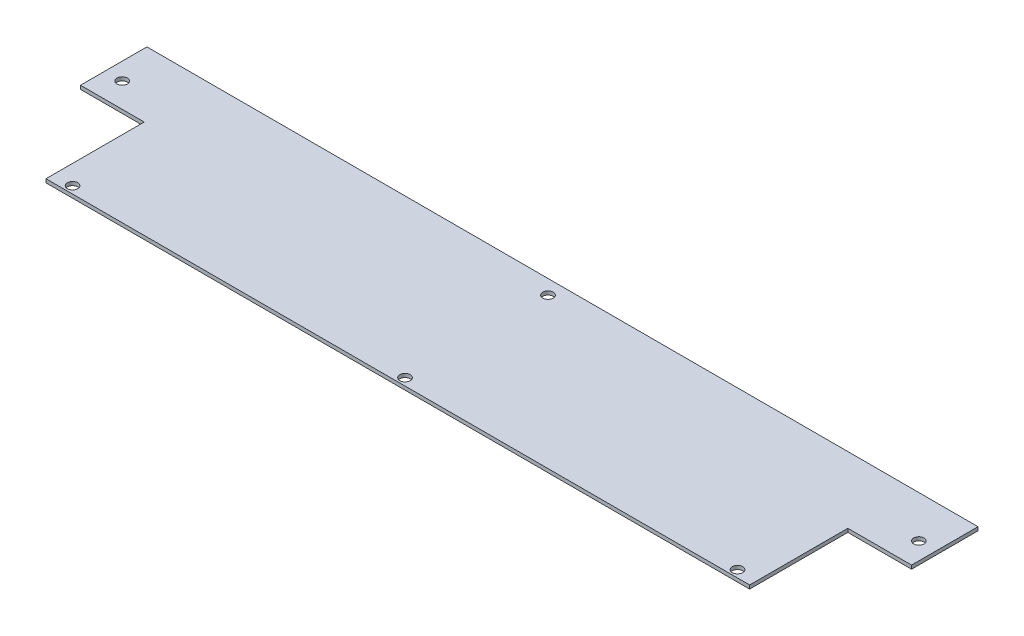
SolidWorks part; units mm, degrees
ref_plane "Front Plane" through (0, 0, 0) normal (0, 0, 1) x (1, 0, 0)
ref_plane "Top Plane" through (0, 0, 0) normal (0, 1, 0) x (1, 0, 0)
ref_plane "Right Plane" through (0, 0, 0) normal (1, 0, 0) x (0, 0, -1)
sketch "Sketch1" plane through (0, 0, 0) normal (0, 1, 0) x (1, 0, 0)
  line L0 (0, 0) -> (0, -33.02) construction
  line L1 (190.5, -36.195) -> (-190.5, -36.195) construction
  line L2 (190.5, -36.195) -> (190.5, 36.195) construction
  line L3 (190.5, 36.195) -> (-190.5, 36.195) construction
  line L4 (-190.5, -36.195) -> (-190.5, 36.195) construction
  line L5 (190.5, -36.195) -> (-190.5, 36.195) construction
  line L6 (190.5, 36.195) -> (-190.5, -36.195) construction
  line L7 (-146.177, -33.02) -> (146.177, -33.02) construction
  line L8 (0, 0) -> (0, 29.845) construction
  line L27 (0, 0) -> (0, 17.78) construction
  line L34 (-175.1457, 17.78) -> (175.1457, 17.78) construction
  line L35 (-154.686, -36.195) -> (-154.686, 6.985)
  line L48 (154.686, -36.195) -> (154.686, 6.985)
  line L49 (154.686, -36.195) -> (-154.686, -36.195)
  line L50 (-154.686, 6.985) -> (-182.7083, 6.985)
  line L52 (-182.7083, 36.195) -> (-182.7083, 6.985)
  line L53 (-182.7083, 36.195) -> (182.7083, 36.195)
  line L54 (182.7083, 36.195) -> (182.7083, 6.985)
  line L55 (182.7083, 6.985) -> (154.686, 6.985)
  circle A0 centre (175.1457, 17.78) radius 2.286
  circle A1 centre (0, 29.845) radius 2.286
  circle A2 centre (146.177, -33.02) radius 2.286
  circle A3 centre (-175.1457, 17.78) radius 2.286
  circle A4 centre (0, -33.02) radius 2.286
  circle A5 centre (-146.177, -33.02) radius 2.286
  point P0 (0, 0)
  point P10 (0, -33.02)
  point P17 (-184.4888, 3.81)
  point P18 (-240.3437, -33.02)
  point P20 (0, 0)
  point P21 (0, 36.195)
  point P22 (0, -36.195)
  point P58 (0, 17.78)
  dimension "D5" = 4.572
  dimension "D1" = 381
  dimension "D2" = 72.39
  dimension "D3" = 33.02
  dimension "D4" = 292.354
  dimension "D6" = 29.845
  dimension "D7" = 17.78
  dimension "D8" = 350.2914
  dimension "D9" = 309.372
  dimension "D11" = 43.18
  dimension "D12" = 43.18
  dimension "D13" = 28.0223
  dimension "D14" = 175.1457
  dimension "D15" = 175.1457
  dimension "D16" = 182.7083
  dimension "D17" = 182.7083
extrude "Boss-Extrude1" add sketch "Sketch1" along normal blind 1.5875
